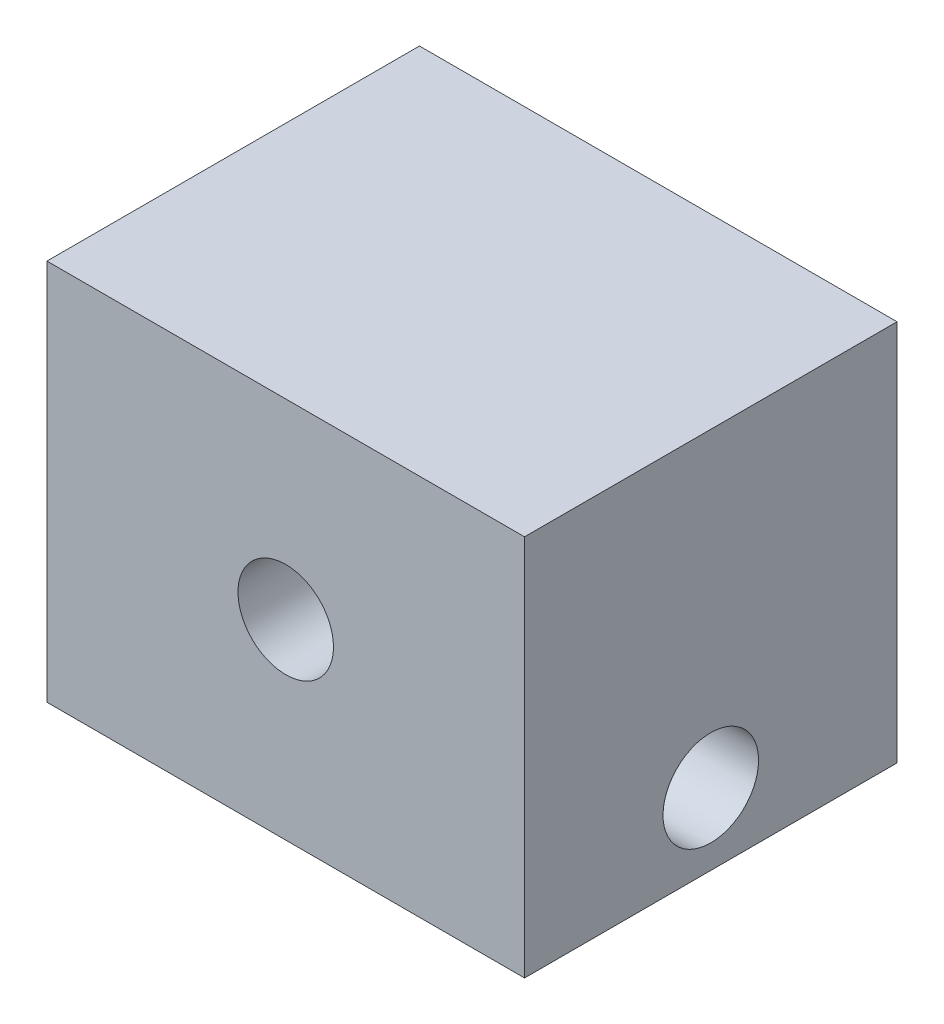
SolidWorks part; units mm, degrees
ref_plane "Спереди" through (0, 0, 0) normal (0, 0, 1) x (1, 0, 0)
ref_plane "Сверху" through (0, 0, 0) normal (0, 1, 0) x (1, 0, 0)
ref_plane "Справа" through (0, 0, 0) normal (1, 0, 0) x (0, 0, -1)
sketch "Эскиз1" plane through (0, 0, 0) normal (0, 0, 1) x (1, 0, 0)
  line L0 (-50, 55) -> (50, 55)
  line L1 (-50, 60.8936) -> (-50, -24.1064) construction
  line L2 (50, 55) -> (50, -25)
  line L3 (50, -25) -> (-50, -25)
  line L4 (-50, -25) -> (-50, 55)
  line L5 (0, 15) -> (50, 15) construction
  line L6 (0, 15) -> (0, 55) construction
  line L7 (0, 15) -> (0, -25) construction
  line L8 (0, 15) -> (-50, 15) construction
  circle A0 centre (0, 15) radius 10 construction
  circle A1 centre (0, 15) radius 10
  dimension "D1" = 40
extrude "Бобышка-Вытянуть1" add sketch "Эскиз1" against normal blind 78
sketch "Эскиз3" plane through (-50, 0, 0) normal (-1, 0, 0) x (0, 0, 1)
  line L1 (-39, -10) -> (-39, -25) construction
  line L2 (-78, -25) -> (0, -25) construction
  line L3 (0, 55) -> (0, -25) construction
  line L4 (-39, -10) -> (0, -10) construction
  line L5 (-39, -10) -> (-78, -10) construction
  line L6 (-78, 55) -> (-78, -25) construction
  circle A0 centre (-39, -10) radius 10
  dimension "D1" = 20
  dimension "D2" = 15
extrude "Вырез-Вытянуть1" cut sketch "Эскиз3" against normal up to next
